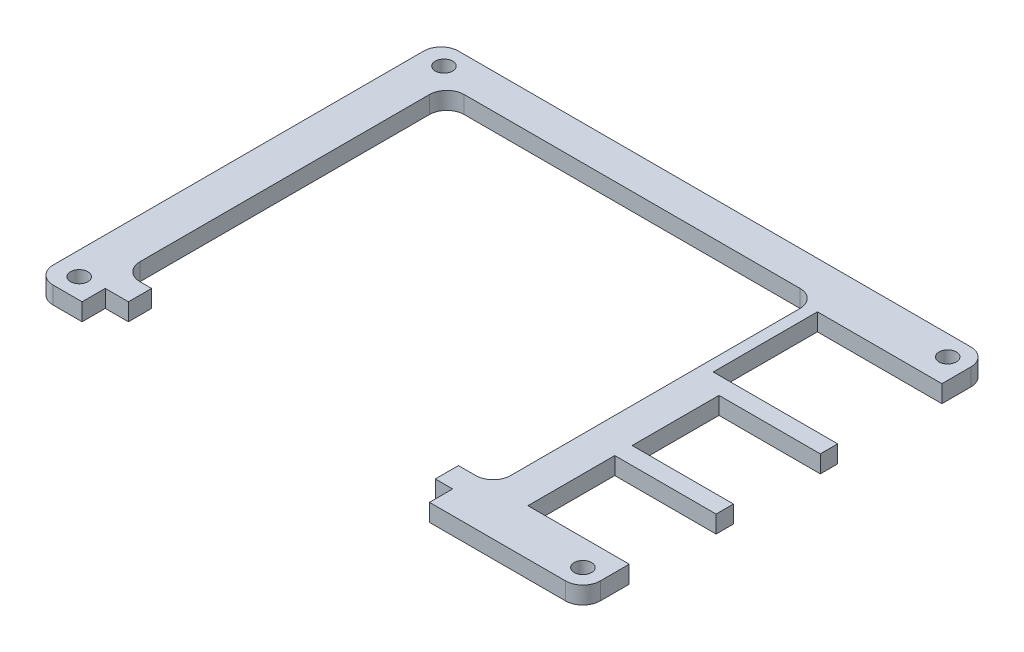
SolidWorks part; units mm, degrees
material "Acrylic (Medium-high impact)"
ref_plane "Front Plane" through (0, 0, 0) normal (0, 0, 1) x (1, 0, 0)
ref_plane "Top Plane" through (0, 0, 0) normal (0, 1, 0) x (1, 0, 0)
ref_plane "Right Plane" through (0, 0, 0) normal (1, 0, 0) x (0, 0, -1)
sketch "Sketch1" plane through (0, 0, 0) normal (0, 1, 0) x (1, 0, 0)
  line L1 (-47.25, 35) -> (47.25, 35)
  line L2 (-47.25, 35) -> (-47.25, -35)
  line L3 (-47.25, -35) -> (47.25, -35)
  line L4 (47.25, 35) -> (47.25, -35)
  line L5 (-47.25, 35) -> (47.25, -35) construction
  line L6 (-47.25, -35) -> (47.25, 35) construction
  point P0 (0, 0)
  dimension "D1" = 70
  dimension "D2" = 94.5
extrude "Boss-Extrude1" add sketch "Sketch1" along normal blind 3
sketch "Sketch3" plane through (0, 3, 0) normal (0, 1, 0) x (1, 0, 0)
  line L0 (47.25, -35) -> (47.25, 35) construction
  line L2 (47.25, 35) -> (-47.25, 35) construction
  circle A0 centre (43.75, 31.5) radius 1.5
  circle A1 centre (-43.25, 31.5) radius 1.5
  circle A2 centre (-43.25, -31.5) radius 1.5
  circle A3 centre (43.75, -31.5) radius 1.5
  dimension "D1" = 3
  dimension "D2" = 3.5
  dimension "D3" = 3.5
  dimension "D4" = 2
  dimension "D5" = 87
  dimension "D6" = 63
  dimension "D7" = 2
extrude "Cut-Extrude2" cut sketch "Sketch3" against normal through all
fillet "Fillet2" radius 3 4 edges at (-47.25, 1.5, 35) (-47.25, 1.5, -35) (47.25, 1.5, -35) (47.25, 1.5, 35)
sketch "Sketch5" plane through (0, 3, 0) normal (0, 1, 0) x (1, 0, 0)
  line L0 (-40.25, 29) -> (23.75, 29)
  line L1 (23.75, 29) -> (23.75, -27)
  line L2 (23.75, -27) -> (-40.25, -27)
  line L3 (-40.25, -27) -> (-40.25, 29)
  line L4 (47.25, 27) -> (25.75, 27)
  line L5 (47.25, -32) -> (47.25, 32) construction
  line L6 (25.75, 27) -> (25.75, 9)
  line L7 (25.75, 9) -> (47.25, 9)
  line L8 (47.25, 9) -> (47.25, 27)
  line L9 (47.25, 6) -> (29.75, 6)
  line L10 (29.75, 6) -> (29.75, -9)
  line L11 (29.75, -9) -> (47.25, -9)
  line L12 (47.25, -9) -> (47.25, 6)
  line L13 (47.25, -12) -> (29.75, -12)
  line L14 (29.75, -12) -> (29.75, -27)
  line L15 (29.75, -27) -> (47.25, -27)
  line L16 (47.25, -27) -> (47.25, -12)
  line L17 (44.25, 35) -> (-44.25, 35) construction
  line L18 (-47.25, 32) -> (-47.25, -32) construction
  line L19 (-35.25, -27) -> (-35.25, -31)
  line L20 (-35.25, -31) -> (-39.25, -31)
  line L21 (-39.25, -31) -> (-39.25, -35)
  line L22 (-44.25, -35) -> (44.25, -35) construction
  line L23 (-39.25, -35) -> (20.75, -35)
  line L24 (20.75, -35) -> (20.75, -31)
  line L25 (20.75, -31) -> (17.75, -31)
  line L26 (17.75, -31) -> (17.75, -27)
  line M19 (-44.25, -35) -> (44.25, -35)
  line M21 (47.25, -32) -> (47.25, 32)
  dimension "D1" = 6
  dimension "D2" = 7
  dimension "D3" = 64
  dimension "D4" = 56
  dimension "D5" = 18
  dimension "D6" = 2
  dimension "D7" = 6
  dimension "D8" = 3
  dimension "D9" = 8
  dimension "D10" = 15
  dimension "D11" = 3
  dimension "D12" = 15
  dimension "D13" = 6
  dimension "D14" = 60
  dimension "D15" = 8
  dimension "D16" = 53
  dimension "D17" = 4
  dimension "D18" = 12
extrude "Cut-Extrude3" cut sketch "Sketch5" against normal through all contours L3 L2 L1 L0 | L6 L7 L4 M21 | L10 L11 L9 M21 | L14 L15 L13 M21 | L25 L26 L2 L19 L20 L21 L24 M19
fillet "Fillet3" radius 3 4 edges at (23.75, 1.5, -29) (23.75, 1.5, 27) (-40.25, 1.5, 27) (-40.25, 1.5, -29)
